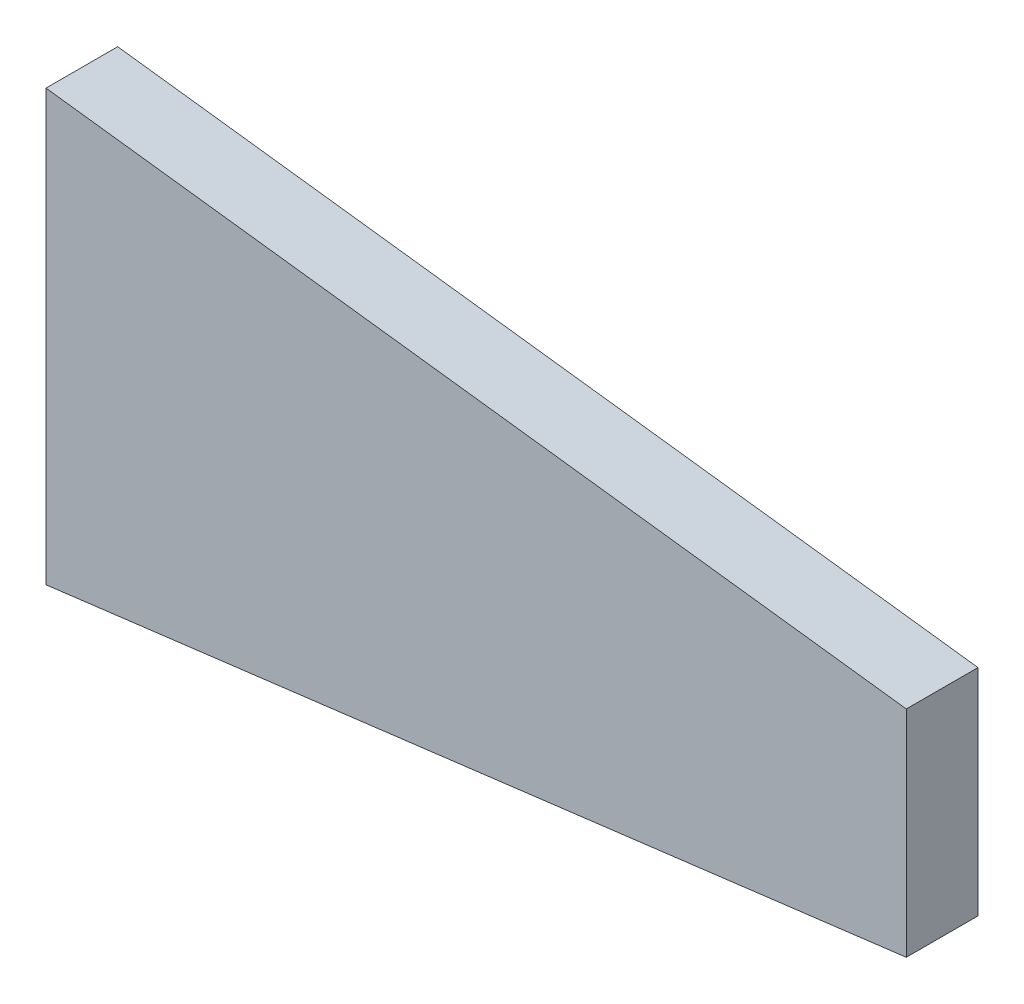
SolidWorks part; units mm, degrees
ref_plane "Front Plane" through (0, 0, 0) normal (0, 0, 1) x (1, 0, 0)
ref_plane "Top Plane" through (0, 0, 0) normal (0, 1, 0) x (1, 0, 0)
ref_plane "Right Plane" through (0, 0, 0) normal (1, 0, 0) x (0, 0, -1)
sketch "Sketch1" plane through (0, 0, 0) normal (0, 0, 1) x (1, 0, 0)
  line L0 (-76.2, 38.1) -> (76.2, 19.05)
  line L1 (76.2, 19.05) -> (76.2, -19.05)
  line L2 (76.2, -19.05) -> (-76.2, -38.1)
  line L3 (-76.2, -38.1) -> (-76.2, 38.1)
  line L4 (0, 0) -> (76.2, 0) construction
  line L5 (0, 0) -> (-76.2, 0) construction
  dimension "D1" = 38.1
  dimension "D2" = 76.2
  dimension "D3" = 152.4
extrude "Boss-Extrude1" add sketch "Sketch1" along normal blind 12.7
